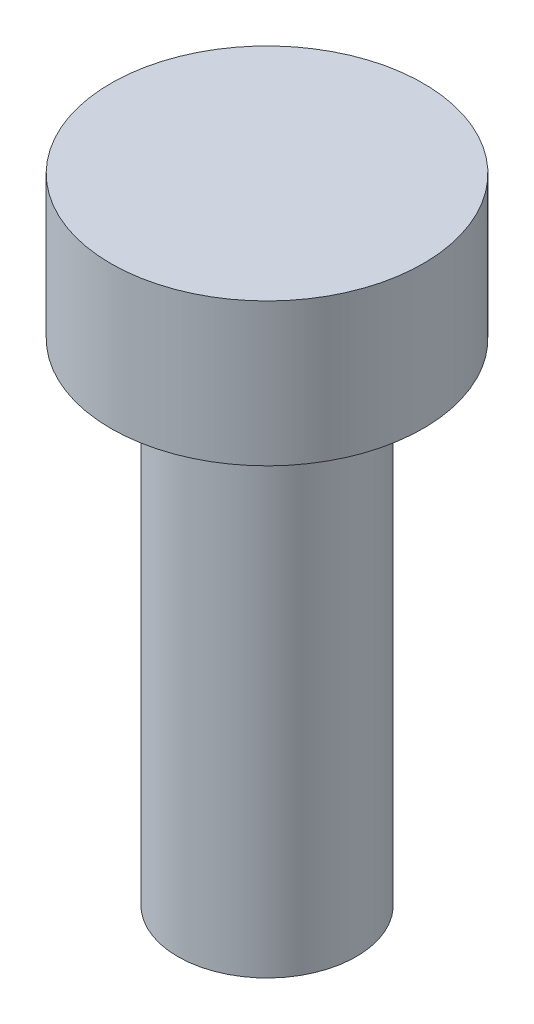
SolidWorks part; units mm, degrees
ref_plane "Plan de face" through (0, 0, 0) normal (0, 0, 1) x (1, 0, 0)
ref_plane "Plan de dessus" through (0, 0, 0) normal (0, 1, 0) x (1, 0, 0)
ref_plane "Plan de droite" through (0, 0, 0) normal (1, 0, 0) x (0, 0, -1)
sketch "Esquisse1" plane through (0, 0, 0) normal (0, 1, 0) x (1, 0, 0)
  circle A0 centre (0, 0) radius 1.75
  dimension "D1" = 3.5
extrude "Boss.-Extru.1" add sketch "Esquisse1" along normal blind 1.6
sketch "Esquisse2" plane through (0, 0, 0) normal (0, -1, 0) x (1, 0, 0)
  circle A0 centre (0, 0) radius 1
  dimension "D1" = 2
extrude "Boss.-Extru.2" add sketch "Esquisse2" along normal blind 5.5
